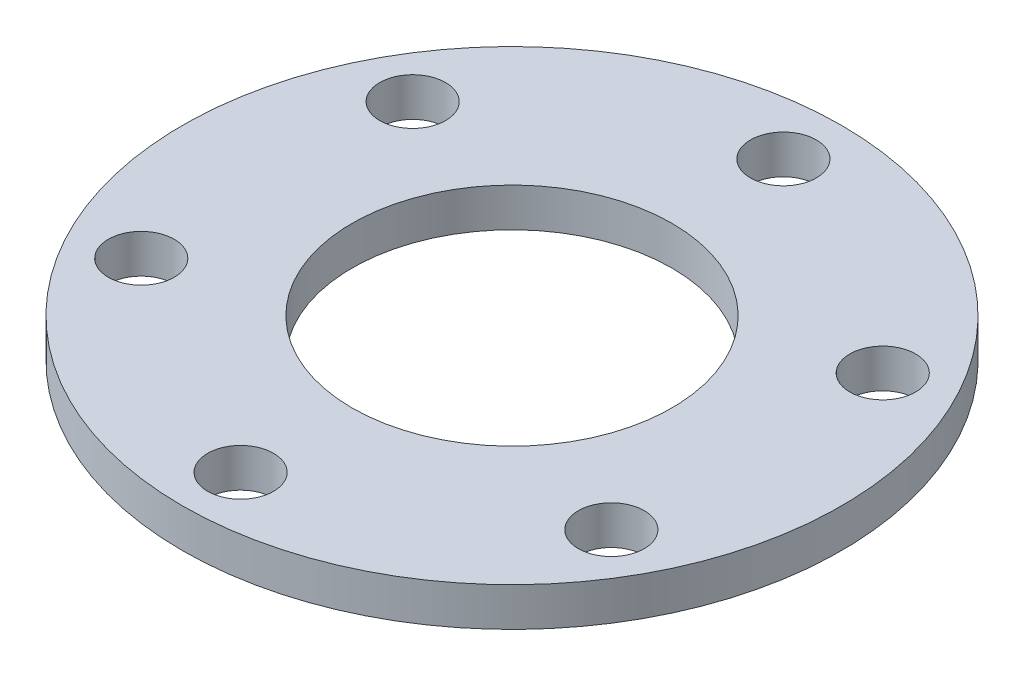
SolidWorks part; units mm, degrees
ref_plane "Front Plane" through (0, 0, 0) normal (0, 0, 1) x (1, 0, 0)
ref_plane "Top Plane" through (0, 0, 0) normal (0, 1, 0) x (1, 0, 0)
ref_plane "Right Plane" through (0, 0, 0) normal (1, 0, 0) x (0, 0, -1)
sketch "Sketch1" plane through (0, 0, 0) normal (0, 1, 0) x (1, 0, 0)
  circle A0 centre (0, 0) radius 17
  circle A1 centre (0, 0) radius 8.25
  circle A2 centre (0, 0) radius 14 construction
  circle A3 centre (0, 14) radius 1.7
  circle A6 centre (0, 0) radius 12 construction
  circle A7 centre (12.1244, 7) radius 1.7
  circle A8 centre (12.1244, -7) radius 1.7
  circle A9 centre (0, -14) radius 1.7
  circle A10 centre (-12.1244, -7) radius 1.7
  circle A11 centre (-12.1244, 7) radius 1.7
  point P13 (0, 0)
  point P21 (0, 0)
  dimension "D1" = 34
  dimension "D2" = 16.5
  dimension "D3" = 28
  dimension "D4" = 3.4
  dimension "D6" = 24
  dimension "D5" = 6
extrude "Boss-Extrude1" add sketch "Sketch1" along normal blind 2
